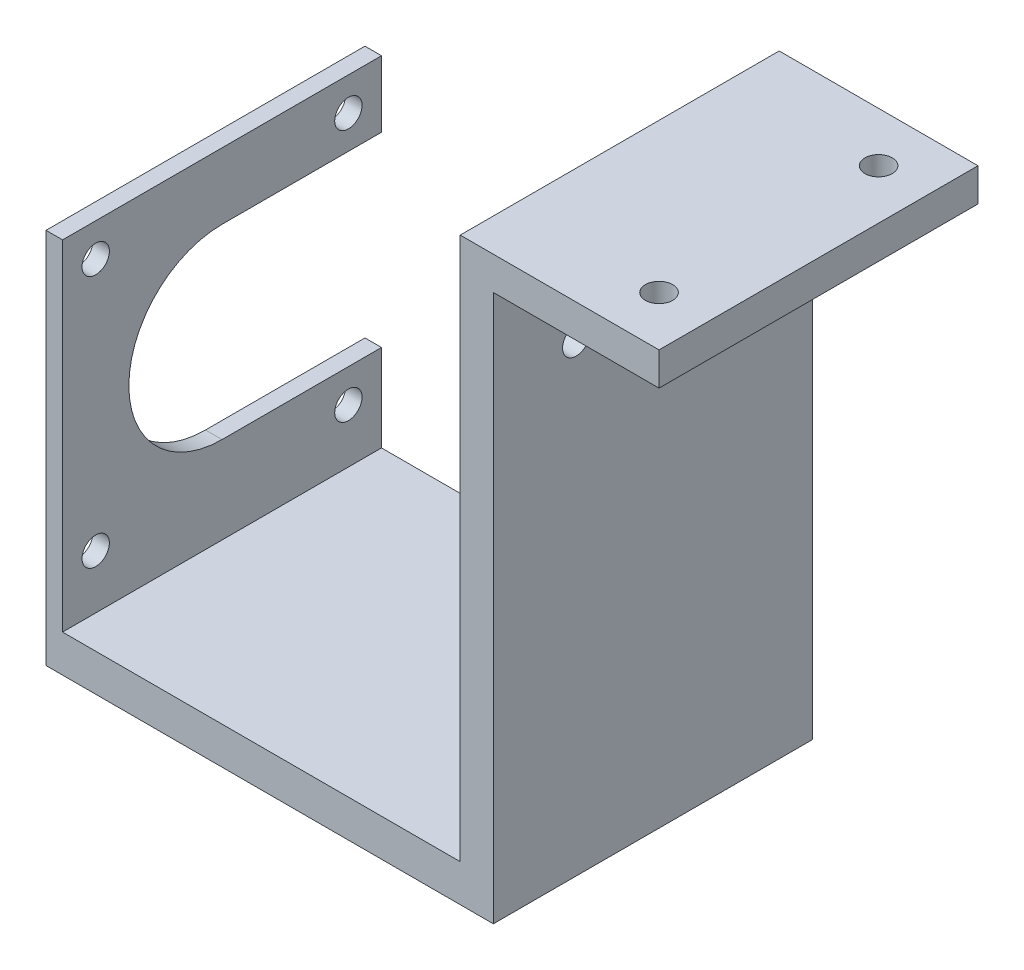
SolidWorks part; units mm, degrees
ref_plane "Front Plane" through (0, 0, 0) normal (0, 0, 1) x (1, 0, 0)
ref_plane "Top Plane" through (0, 0, 0) normal (0, 1, 0) x (1, 0, 0)
ref_plane "Right Plane" through (0, 0, 0) normal (1, 0, 0) x (0, 0, -1)
sketch "Sketch1" plane through (0, 0, 0) normal (1, 0, 0) x (0, 0, -1)
  line L1 (0, 0) -> (13, 0)
  line L2 (0, 0) -> (0, -16)
  line L3 (0, -16) -> (13, -16)
  line L4 (13, 0) -> (13, -16)
  dimension "D1" = 13
  dimension "D2" = 16
extrude "Boss-Extrude1" add sketch "Sketch1" along normal blind 4
sketch "Sketch2" plane through (4, 0, 0) normal (1, 0, 0) x (0, 0, -1)
  line L0 (13, 0) -> (0, 0) construction
  line L1 (0, -16) -> (13, -16) construction
  line L2 (13, -16) -> (13, 0) construction
  line L3 (0, 0) -> (0, -16) construction
  circle A0 centre (6.5, -4) radius 1.65
  circle A1 centre (6.5, -12) radius 1.65
  dimension "D1" = 3.3
  dimension "D2" = 3.3
  dimension "D3" = 4
  dimension "D4" = 4
  dimension "D5" = 6.5
  dimension "D6" = 6.5
extrude "Cut-Extrude1" cut sketch "Sketch2" against normal blind 10
sketch "Sketch3" plane through (0, -16, 0) normal (0, -1, 0) x (1, 0, 0)
  line L1 (4, 0) -> (0, 0)
  line L2 (4, 0) -> (4, -13)
  line L3 (4, -13) -> (0, -13)
  line L4 (0, 0) -> (0, -13)
extrude "Boss-Extrude2" add sketch "Sketch3" along normal blind 4
sketch "Sketch4" plane through (4, 0, 0) normal (1, 0, 0) x (0, 0, -1)
  line L0 (13, -20) -> (13, 0) construction
  line L1 (0, -20) -> (13, -20)
  line L2 (0, -20) -> (0, -16)
  line L3 (0, -16) -> (13, -16)
  line L4 (13, -20) -> (13, -16)
  dimension "D1" = 4
extrude "Boss-Extrude3" add sketch "Sketch4" along normal blind 60
sketch "Sketch6" plane through (0, -16, 0) normal (0, 1, 0) x (1, 0, 0)
  line L0 (64, 0) -> (4, 0) construction
  line L1 (64, 13) -> (60, 13)
  line L2 (64, 13) -> (64, -21)
  line L3 (64, -21) -> (60, -21)
  line L4 (60, 13) -> (60, -21)
  line L7 (64, 13) -> (60, 13)
  line L8 (64, 13) -> (64, 34)
  line L9 (64, 34) -> (60, 34)
  line L10 (60, 13) -> (60, 34)
  line M2 (4, 0) -> (64, 0)
  line M3 (64, 0) -> (64, 13)
  line M4 (64, 13) -> (4, 13)
  dimension "D1" = 4
  dimension "D2" = 21
  dimension "D3" = 21
extrude "Boss-Extrude4" add sketch "Sketch6" along normal blind 28 contours L4 L3 L2 M2 | L10 L8 L9 M4 | L4 M4 M2 M3
sketch "Sketch12" plane through (0, 0, -34) normal (0, 0, -1) x (-1, 0, 0)
  line L1 (-60, -16) -> (-64, -16)
  line L2 (-60, -16) -> (-60, 12)
  line L3 (-60, 12) -> (-64, 12)
  line L4 (-64, -16) -> (-64, 12)
extrude "Boss-Extrude8" add sketch "Sketch12" along normal blind 1.65
sketch "Sketch13" plane through (0, 0, 21) normal (0, 0, 1) x (1, 0, 0)
  line L1 (60, 12) -> (64, 12)
  line L2 (60, 12) -> (60, -16)
  line L3 (60, -16) -> (64, -16)
  line L4 (64, 12) -> (64, -16)
extrude "Boss-Extrude9" add sketch "Sketch13" along normal blind 1.65
sketch "Sketch14" plane through (0, 12, 0) normal (0, 1, 0) x (1, 0, 0)
  line L0 (64, 35.65) -> (64, -22.65) construction
  line L1 (64, 24.35) -> (60, 24.35)
  line L2 (64, 24.35) -> (64, -11.5284)
  line L3 (64, -11.5284) -> (60, -11.5284)
  line L4 (60, 24.35) -> (60, -11.5284)
  line L5 (60, 35.65) -> (60, -22.65) construction
  line L6 (64, -22.65) -> (60, -22.65) construction
  line L7 (60, 35.65) -> (64, 35.65) construction
  point P10 (62, -22.65)
  dimension "D1" = 11.3
  dimension "D2" = 11.3
extrude "Cut-Extrude5" cut sketch "Sketch14" against normal blind 24
sketch "Sketch15" plane through (64, 0, 0) normal (1, 0, 0) x (0, 0, -1)
  line L0 (-11.5284, 12) -> (-22.65, 12) construction
  line L1 (35.65, 12) -> (24.35, 12) construction
  line L2 (-22.65, -16) -> (-22.65, 12) construction
  line L3 (35.65, 12) -> (35.65, -16) construction
  circle A0 centre (-17, -11.5) radius 1.65
  circle A1 centre (30, -11.5) radius 1.65
  dimension "D1" = 3.3
  dimension "D2" = 3.3
  dimension "D3" = 23.5
  dimension "D4" = 23.5
  dimension "D5" = 5.65
  dimension "D6" = 5.65
extrude "Cut-Extrude6" cut sketch "Sketch15" against normal blind 24
sketch "Sketch16" plane through (0, 12, 0) normal (0, 1, 0) x (1, 0, 0)
  line L1 (60, -22.65) -> (64, -22.65)
  line L2 (60, -22.65) -> (60, -11.5284)
  line L3 (60, -11.5284) -> (64, -11.5284)
  line L4 (64, -22.65) -> (64, -11.5284)
  line L5 (60, 24.35) -> (64, 24.35)
  line L6 (60, 24.35) -> (60, 35.65)
  line L7 (60, 35.65) -> (64, 35.65)
  line L8 (64, 24.35) -> (64, 35.65)
extrude "Boss-Extrude10" add sketch "Sketch16" along normal blind 29.15
sketch "Sketch17" plane through (64, 0, 0) normal (1, 0, 0) x (0, 0, -1)
  line L0 (-22.65, -16) -> (-22.65, 41.15) construction
  line L1 (35.65, 41.15) -> (35.65, -16) construction
  line L2 (-22.65, 41.15) -> (-11.5284, 41.15) construction
  line L3 (24.35, 41.15) -> (35.65, 41.15) construction
  circle A0 centre (-17, 35.5) radius 1.65
  circle A1 centre (30, 35.5) radius 1.65
  dimension "D1" = 3.3
  dimension "D2" = 3.3
  dimension "D4" = 5.65
  dimension "D3" = 5.65
  dimension "D5" = 5.65
  dimension "D6" = 5.65
extrude "Cut-Extrude8" cut sketch "Sketch17" against normal blind 29.15
sketch "Sketch18" plane through (64, 0, 0) normal (1, 0, 0) x (0, 0, -1)
  line L1 (-22.65, -16) -> (13, -16)
  line L2 (-22.65, -16) -> (-22.65, -20)
  line L3 (-22.65, -20) -> (13, -20)
  line L4 (13, -16) -> (13, -20)
  line L5 (0, -20) -> (35.65, -20)
  line L6 (0, -20) -> (0, -16)
  line L7 (0, -16) -> (35.65, -16)
  line L8 (35.65, -20) -> (35.65, -16)
  line M9 (-22.65, -16) -> (0, -16)
  line M10 (0, -16) -> (0, -20)
  line M11 (0, -20) -> (13, -20)
  line M12 (13, -20) -> (13, -16)
  line M13 (13, -16) -> (35.65, -16)
extrude "Boss-Extrude11" add sketch "Sketch18" against normal blind 4 contours L2 L3 M10 M9 | L5 L8 M13 M12 | L1 M10 M11 M12
sketch "Sketch19" plane through (0, 0, -13) normal (0, 0, -1) x (-1, 0, 0)
  line L1 (0, -20) -> (-4, -20)
  line L2 (0, -20) -> (0, 0)
  line L3 (0, 0) -> (-4, 0)
  line L4 (-4, -20) -> (-4, 0)
extrude "Boss-Extrude12" add sketch "Sketch19" along normal blind 40
sketch "Sketch20" plane through (0, 0, 0) normal (-1, 0, 0) x (0, 0, 1)
  line L0 (-53, 0) -> (0, 0) construction
  line L1 (-53, -20) -> (-53, 0) construction
  circle A0 centre (-46.5, -4) radius 1.65
  circle A1 centre (-46.5, -12) radius 1.65
  dimension "D1" = 3.3
  dimension "D2" = 3.3
  dimension "D3" = 4
  dimension "D4" = 8
  dimension "D5" = 6.5
  dimension "D6" = 6.5
extrude "Cut-Extrude9" cut sketch "Sketch20" against normal blind 40
sketch "Sketch21" plane through (0, -16, 0) normal (0, 1, 0) x (1, 0, 0)
  line L0 (4, 53) -> (4, 13) construction
  line L1 (28, 21.75) -> (24, 21.75)
  line L2 (28, 21.75) -> (28, -8.75)
  line L3 (28, -8.75) -> (24, -8.75)
  line L4 (24, 21.75) -> (24, -8.75)
  line L5 (60, 13) -> (4, 13) construction
  line L6 (60, 0) -> (4, 0) construction
  dimension "D1" = 20
  dimension "D2" = 4
  dimension "D3" = 8.75
  dimension "D4" = 8.75
extrude "Boss-Extrude13" add sketch "Sketch21" along normal blind 38.5
sketch "Sketch23" plane through (0, 22.5, 0) normal (0, 1, 0) x (1, 0, 0)
  line L1 (24, 21.75) -> (28, 21.75)
  line L2 (24, 21.75) -> (24, 25.75)
  line L3 (24, 25.75) -> (28, 25.75)
  line L4 (28, 21.75) -> (28, 25.75)
  line L6 (24, 21.75) -> (24, -8.75) construction
  line L7 (28, -8.75) -> (28, 21.75) construction
  line L8 (24, -8.75) -> (28, -8.75)
  line L9 (24, -8.75) -> (24, -12.75)
  line L10 (24, -12.75) -> (28, -12.75)
  line L11 (28, -8.75) -> (28, -12.75)
  dimension "D1" = 4
  dimension "D2" = 4
  dimension "D3" = 4
  dimension "D4" = 0
extrude "Boss-Extrude14" add sketch "Sketch23" against normal blind 38.5
sketch "Sketch24" plane through (0, 22.5, 0) normal (0, 1, 0) x (1, 0, 0)
  line L1 (28, 25.75) -> (24, 25.75)
  line L2 (28, 25.75) -> (28, -12.75)
  line L3 (28, -12.75) -> (24, -12.75)
  line L4 (24, 25.75) -> (24, -12.75)
extrude "Boss-Extrude15" add sketch "Sketch24" along normal blind 3
sketch "Sketch25" plane through (28, 0, 0) normal (1, 0, 0) x (0, 0, -1)
  line L0 (25.75, -16) -> (25.75, 25.5) construction
  line L1 (25.75, -13) -> (-12.75, -13)
  line L2 (25.75, -13) -> (25.75, -20)
  line L3 (25.75, -20) -> (-12.75, -20)
  line L4 (-12.75, -13) -> (-12.75, -20)
  line L5 (13, -16) -> (25.75, -16) construction
  line L6 (-12.75, -16) -> (0, -16) construction
  line L7 (-12.75, -16) -> (-12.75, 25.5) construction
  dimension "D1" = 3
  dimension "D2" = 4
  dimension "D3" = 0
sketch "Sketch27" plane through (0, -20, 0) normal (0, -1, 0) x (1, 0, 0)
  line L1 (64, 22.65) -> (60, 22.65)
  line L2 (64, 22.65) -> (64, -35.65)
  line L3 (64, -35.65) -> (60, -35.65)
  line L4 (60, 22.65) -> (60, -35.65)
extrude "Cut-Extrude10" cut sketch "Sketch27" against normal blind 100
sketch "Sketch29" plane through (28, 0, 0) normal (1, 0, 0) x (0, 0, -1)
  line L2 (-12.75, -13) -> (25.75, -13)
  line L3 (-12.75, -13) -> (-12.75, -20)
  line L4 (-12.75, -20) -> (25.75, -20)
  line L5 (25.75, -13) -> (25.75, -20)
extrude "Boss-Extrude16" add sketch "Sketch29" along normal blind 40 and the other way blind 28
sketch "Sketch30" plane through (24, 0, 0) normal (-1, 0, 0) x (0, 0, 1)
  line L0 (12.75, -13) -> (12.75, 25.5) construction
  line L1 (-25.75, 25.5) -> (12.75, 25.5) construction
  line L2 (-25.75, -13) -> (12.75, -13) construction
  line L3 (-25.75, -13) -> (-25.75, 25.5) construction
  circle A0 centre (8.75, 21.5) radius 1.65
  circle A1 centre (8.75, -9) radius 1.65
  circle A2 centre (-21.75, 21.5) radius 1.65
  circle A3 centre (-21.75, -9) radius 1.65
  dimension "D1" = 3.3
  dimension "D4" = 3.3
  dimension "D7" = 3.3
  dimension "D12" = 3.3
  dimension "D2" = 4
  dimension "D3" = 4
  dimension "D5" = 4
  dimension "D6" = 4
  dimension "D8" = 4
  dimension "D9" = 4
  dimension "D10" = 4
  dimension "D11" = 4
extrude "Cut-Extrude11" cut sketch "Sketch30" against normal blind 40
sketch "Sketch31" plane through (0, 25.5, 0) normal (0, 1, 0) x (1, 0, 0)
  line L0 (28, -12.75) -> (28, 25.75) construction
  line L1 (28, 17.75) -> (24, 17.75)
  line L2 (28, 17.75) -> (28, -4.75)
  line L3 (28, -4.75) -> (24, -4.75)
  line L4 (24, 17.75) -> (24, -4.75)
  line L5 (24, 25.75) -> (24, -12.75) construction
  line L6 (24, -12.75) -> (28, -12.75) construction
  dimension "D1" = 8
  dimension "D2" = 8
extrude "Cut-Extrude12" cut sketch "Sketch31" against normal blind 38.5
sketch "Sketch32" plane through (68, 0, 0) normal (1, 0, 0) x (0, 0, -1)
  line L0 (25.75, -20) -> (25.75, -13) construction
  line L1 (-12.75, -13) -> (25.75, -13)
  line L2 (-12.75, -13) -> (-12.75, -15.5)
  line L3 (-12.75, -15.5) -> (25.75, -15.5)
  line L4 (25.75, -13) -> (25.75, -15.5)
  dimension "D1" = 2.5
extrude "Cut-Extrude13" cut sketch "Sketch32" against normal blind 40
sketch "Sketch33" plane through (0, 25.5, 0) normal (0, 1, 0) x (1, 0, 0)
  line L1 (24, -12.75) -> (28, -12.75)
  line L2 (24, -12.75) -> (24, -4.75)
  line L3 (24, -4.75) -> (28, -4.75)
  line L4 (28, -12.75) -> (28, -4.75)
  line L5 (24, 17.75) -> (28, 17.75)
  line L6 (24, 17.75) -> (24, 25.75)
  line L7 (24, 25.75) -> (28, 25.75)
  line L8 (28, 17.75) -> (28, 25.75)
extrude "Boss-Extrude17" add sketch "Sketch33" against normal blind 8
sketch "Sketch34" plane through (28, 0, 0) normal (1, 0, 0) x (0, 0, -1)
  line L0 (-12.75, 25.5) -> (-4.75, 25.5) construction
  line L1 (-12.75, -15.5) -> (-12.75, 25.5) construction
  line L2 (25.75, -15.5) -> (25.75, 25.5) construction
  line L3 (17.75, 25.5) -> (25.75, 25.5) construction
  circle A0 centre (-8.75, 21.5) radius 1.65
  circle A1 centre (21.75, 21.5) radius 1.65
  dimension "D1" = 3.3
  dimension "D2" = 3.3
  dimension "D3" = 4
  dimension "D4" = 4
  dimension "D5" = 4
  dimension "D6" = 4
extrude "Cut-Extrude14" cut sketch "Sketch34" against normal blind 8
sketch "Sketch35" plane through (0, -13, 0) normal (0, 1, 0) x (1, 0, 0)
  line L0 (0, -12.75) -> (24, -12.75) construction
  line L1 (10, -12.75) -> (14, -12.75)
  line L2 (10, -12.75) -> (10, 30.75)
  line L3 (10, 30.75) -> (14, 30.75)
  line L4 (14, -12.75) -> (14, 30.75)
  line L5 (24, 25.75) -> (24, 17.75) construction
  line L6 (4, 25.75) -> (24, 25.75) construction
  dimension "D1" = 10
  dimension "D2" = 4
  dimension "D3" = 5
extrude "Boss-Extrude18" add sketch "Sketch35" along normal blind 13
sketch "Sketch36" plane through (0, -20, 0) normal (0, -1, 0) x (1, 0, 0)
  line L1 (0, 12.75) -> (68, 12.75) construction
  line L2 (0, 12.75) -> (10, 12.75)
  line L3 (0, 12.75) -> (0, -67.25)
  line L4 (0, -67.25) -> (10, -67.25)
  line L5 (10, 12.75) -> (10, -67.25)
  line L6 (4, -53) -> (4, -25.75) construction
  dimension "D1" = 10
  dimension "D2" = 80
  dimension "D3" = 4
extrude "Cut-Extrude15" cut sketch "Sketch36" against normal up to vertex
sketch "Sketch37" plane through (10, 0, 0) normal (-1, 0, 0) x (0, 0, 1)
  line L1 (-30.75, -13) -> (-25.75, -13)
  line L2 (-30.75, -13) -> (-30.75, -20)
  line L3 (-30.75, -20) -> (-25.75, -20)
  line L4 (-25.75, -13) -> (-25.75, -20)
extrude "Boss-Extrude19" add sketch "Sketch37" against normal blind 4
sketch "Sketch41" plane through (14, 0, 0) normal (1, 0, 0) x (0, 0, -1)
  line L1 (25.75, -20) -> (38.75, -20)
  line L2 (25.75, -20) -> (25.75, 0)
  line L3 (25.75, 0) -> (38.75, 0)
  line L4 (38.75, -20) -> (38.75, 0)
  dimension "D1" = 13
  dimension "D2" = 20
extrude "Boss-Extrude20" add sketch "Sketch41" against normal blind 4
sketch "Sketch42" plane through (10, 0, 0) normal (-1, 0, 0) x (0, 0, 1)
  line L0 (-38.75, 0) -> (12.75, 0) construction
  line L1 (-38.75, -20) -> (-38.75, 0) construction
  circle A0 centre (-32.25, -4) radius 1.65
  circle A1 centre (-32.25, -12) radius 1.65
  dimension "D1" = 3.3
  dimension "D2" = 3.3
  dimension "D3" = 4
  dimension "D4" = 6.5
  dimension "D5" = 8
  dimension "D6" = 6.5
extrude "Cut-Extrude18" cut sketch "Sketch42" against normal blind 4
sketch "Sketch43" plane through (0, 0, 0) normal (0, 1, 0) x (1, 0, 0)
  line L0 (10, 38.75) -> (10, -12.75) construction
  line L1 (14, -12.75) -> (10, -12.75)
  line L2 (14, -12.75) -> (14, 25.75)
  line L3 (14, 25.75) -> (10, 25.75)
  line L4 (10, -12.75) -> (10, 25.75)
  line L5 (10, 38.75) -> (14, 38.75) construction
  dimension "D1" = 13
extrude "Cut-Extrude19" cut sketch "Sketch43" against normal blind 10
sketch "Sketch44" plane through (28, 0, 0) normal (1, 0, 0) x (0, 0, -1)
  line L0 (-4.75, -13) -> (-4.75, 25.5) construction
  line L1 (-12.75, -15.5) -> (-4.75, -15.5)
  line L2 (-12.75, -15.5) -> (-12.75, -6.5)
  line L3 (-12.75, -6.5) -> (-4.75, -6.5)
  line L4 (-4.75, -15.5) -> (-4.75, -6.5)
  line L5 (17.75, -13) -> (17.75, 25.5) construction
  line L6 (25.75, -15.5) -> (17.75, -15.5)
  line L7 (25.75, -15.5) -> (25.75, -6.5)
  line L8 (25.75, -6.5) -> (17.75, -6.5)
  line L9 (17.75, -15.5) -> (17.75, -6.5)
  dimension "D1" = 9
  dimension "D2" = 9
extrude "Boss-Extrude21" add sketch "Sketch44" against normal blind 4
sketch "Sketch45" plane through (24, 0, 0) normal (-1, 0, 0) x (0, 0, 1)
  line L0 (4.75, -13) -> (12.75, -13) construction
  line L1 (-25.75, -13) -> (-17.75, -13) construction
  line L2 (-25.75, -13) -> (-25.75, 25.5) construction
  line L3 (12.75, -13) -> (12.75, 25.5) construction
  circle A0 centre (-21.75, -7) radius 1.65
  circle A1 centre (8.75, -7) radius 1.65
  dimension "D1" = 3.3
  dimension "D2" = 3.3
  dimension "D3" = 6
  dimension "D4" = 6
  dimension "D5" = 4
  dimension "D6" = 4
extrude "Cut-Extrude20" cut sketch "Sketch45" against normal blind 4
sketch "Sketch46" plane through (0, -15.5, 0) normal (0, 1, 0) x (1, 0, 0)
  line L0 (68, -12.75) -> (68, 25.75) construction
  line L1 (64, 18.2859) -> (67, 20.0179)
  line L2 (67, 20.0179) -> (67, 23.4821)
  line L3 (67, 23.4821) -> (64, 25.2141)
  line L4 (64, 25.2141) -> (61, 23.4821)
  line L5 (61, 23.4821) -> (61, 20.0179)
  line L6 (61, 20.0179) -> (64, 18.2859)
  line L7 (64, -12.2141) -> (67, -10.4821)
  line L8 (67, -10.4821) -> (67, -7.0179)
  line L9 (67, -7.0179) -> (64, -5.2859)
  line L10 (64, -5.2859) -> (61, -7.0179)
  line L11 (61, -7.0179) -> (61, -10.4821)
  line L12 (61, -10.4821) -> (64, -12.2141)
  line L13 (28, 25.75) -> (68, 25.75) construction
  line L14 (28, -12.75) -> (68, -12.75) construction
  circle A0 centre (64, 21.75) radius 3 construction
  circle A1 centre (64, -8.75) radius 3 construction
  dimension "D3" = 6
  dimension "D7" = 6
  dimension "D1" = 4
  dimension "D2" = 4
  dimension "D4" = 1
  dimension "D5" = 4
  dimension "D6" = 4
  dimension "D8" = 1
extrude "Cut-Extrude21" cut sketch "Sketch46" against normal blind 3
sketch "Sketch49" plane through (0, -15.5, 0) normal (0, 1, 0) x (1, 0, 0)
  line L0 (68, -12.75) -> (68, 25.75) construction
  line L1 (28, 25.75) -> (68, 25.75) construction
  line L2 (28, -12.75) -> (68, -12.75) construction
  circle A0 centre (64, 21.75) radius 1.65
  circle A1 centre (64, -8.75) radius 1.65
  dimension "D1" = 3.3
  dimension "D2" = 3.3
  dimension "D3" = 4
  dimension "D4" = 4
  dimension "D5" = 4
  dimension "D6" = 4
extrude "Cut-Extrude22" cut sketch "Sketch49" against normal blind 5
ref_plane "Plane1" through (10, -10, -25.75) normal (0, 0, 1) x (1, 0, 0)
sketch "Sketch54" plane through (0, -10, 0) normal (0, 1, 0) x (1, 0, 0)
  line L0 (10, -12.75) -> (14, -12.75) construction
  line L1 (10, 25.75) -> (11, 25.75)
  line L2 (10, 25.75) -> (10, -12.75)
  line L3 (10, -12.75) -> (11, -12.75)
  line L4 (11, 25.75) -> (11, -12.75)
  dimension "D1" = 1
  dimension "D2" = 0
extrude "Cut-Extrude24" cut sketch "Sketch54" against normal blind 50
sketch "Sketch55" plane through (24, 0, 0) normal (-1, 0, 0) x (0, 0, 1)
  line L0 (4.75, -13) -> (4.75, 25.5) construction
  line L1 (12.75, -13) -> (4.75, -13)
  line L2 (12.75, -13) -> (12.75, -3)
  line L3 (12.75, -3) -> (4.75, -3)
  line L4 (4.75, -13) -> (4.75, -3)
  line L5 (-25.75, -13) -> (-25.75, 25.5) construction
  line L6 (-17.75, -13) -> (-25.75, -13)
  line L7 (-17.75, -13) -> (-17.75, -3)
  line L8 (-17.75, -3) -> (-25.75, -3)
  line L9 (-25.75, -13) -> (-25.75, -3)
  dimension "D1" = 10
  dimension "D2" = 10
extrude "Boss-Extrude22" add sketch "Sketch55" against normal blind 4
sketch "Sketch56" plane through (24, 0, 0) normal (-1, 0, 0) x (0, 0, 1)
  line L0 (-17.75, -13) -> (-17.75, 25.5) construction
  line L1 (4.75, -13) -> (4.75, 25.5) construction
  circle A0 centre (-21.75, -9) radius 1.65
  circle A1 centre (8.75, -9) radius 1.65
  circle A2 centre (-21.75, 21.5) radius 1.65 construction
  circle A3 centre (8.75, 21.5) radius 1.65 construction
  dimension "D3" = 3.3
  dimension "D4" = 3.3
  dimension "D1" = 30.5
  dimension "D2" = 30.5
  dimension "D5" = 4
  dimension "D6" = 4
extrude "Cut-Extrude25" cut sketch "Sketch56" against normal blind 4
sketch "Sketch57" plane through (0, -13, 0) normal (0, 1, 0) x (1, 0, 0)
  line L1 (24, -12.75) -> (-1, -12.75)
  line L2 (24, -12.75) -> (24, 57.25)
  line L3 (24, 57.25) -> (-1, 57.25)
  line L4 (-1, -12.75) -> (-1, 57.25)
  dimension "D1" = 70
  dimension "D2" = 25
extrude "Cut-Extrude26" cut sketch "Sketch57" against normal blind 10 and the other way blind 15
sketch "Sketch58" plane through (0, -20, 0) normal (0, -1, 0) x (1, 0, 0)
  line L0 (28, -25.75) -> (28, 12.75) construction
  line L1 (28, -25.75) -> (75.5, -25.75)
  line L2 (28, -25.75) -> (28, 12.75)
  line L3 (28, 12.75) -> (75.5, 12.75)
  line L4 (75.5, -25.75) -> (75.5, 12.75)
  line L5 (24, -25.75) -> (68, -25.75) construction
  dimension "D1" = 38.5
  dimension "D2" = 47.5
extrude "Boss-Extrude24" add sketch "Sketch58" against normal blind 4.5
sketch "Sketch59" plane through (0, -20, 0) normal (0, -1, 0) x (1, 0, 0)
  line L0 (24, -25.75) -> (75.5, -25.75) construction
  line L1 (75.5, 12.75) -> (76, 12.75)
  line L2 (75.5, 12.75) -> (75.5, -25.75)
  line L3 (75.5, -25.75) -> (76, -25.75)
  line L4 (76, 12.75) -> (76, -25.75)
  dimension "D1" = 0
  dimension "D2" = 0.5
extrude "Boss-Extrude25" add sketch "Sketch59" against normal blind 4.5
sketch "Sketch60" plane through (0, -20, 0) normal (0, -1, 0) x (1, 0, 0)
  line L0 (24, -25.75) -> (76, -25.75) construction
  line L1 (76, 12.75) -> (80, 12.75)
  line L2 (76, 12.75) -> (76, -25.75)
  line L3 (76, -25.75) -> (80, -25.75)
  line L4 (80, 12.75) -> (80, -25.75)
  dimension "D1" = 0
  dimension "D2" = 4
extrude "Boss-Extrude26" add sketch "Sketch60" against normal blind 69.5
sketch "Sketch61" plane through (80, 0, 0) normal (1, 0, 0) x (0, 0, -1)
  line L0 (-12.75, 49.5) -> (-12.75, -20) construction
  line L1 (25.75, 49.5) -> (-12.75, 49.5)
  line L2 (25.75, 49.5) -> (25.75, 47.0423)
  line L3 (25.75, 47.0423) -> (-12.75, 47.0423)
  line L4 (-12.75, 49.5) -> (-12.75, 47.0423)
extrude "Boss-Extrude27" add sketch "Sketch61" along normal blind 20
sketch "Sketch62" plane through (76, 0, 0) normal (-1, 0, 0) x (0, 0, 1)
  line L0 (12.75, 49.5) -> (12.75, -15.5) construction
  line L1 (12.75, 28) -> (-25.75, 28)
  line L2 (12.75, 28) -> (12.75, 30)
  line L3 (12.75, 30) -> (-25.75, 30)
  line L4 (-25.75, 28) -> (-25.75, 30)
  line L5 (-25.75, 49.5) -> (-25.75, -15.5) construction
  line L6 (-25.75, -15.5) -> (12.75, -15.5) construction
  dimension "D1" = 43.5
  dimension "D2" = 2
extrude "Boss-Extrude31" add sketch "Sketch62" along normal blind 29.5
sketch "Sketch64" plane through (0, 30, 0) normal (0, 1, 0) x (1, 0, 0)
  line L0 (46.5, -12.75) -> (46.5, 25.75) construction
  line L1 (46.5, 0) -> (50.5, 0)
  line L2 (46.5, 0) -> (46.5, 13)
  line L3 (46.5, 13) -> (50.5, 13)
  line L4 (50.5, 0) -> (50.5, 13)
  line L5 (46.5, -12.75) -> (76, -12.75) construction
  dimension "D1" = 12.75
  dimension "D2" = 13
  dimension "D3" = 4
extrude "Boss-Extrude32" add sketch "Sketch64" along normal blind 16
sketch "Sketch65" plane through (46.5, 0, 0) normal (-1, 0, 0) x (0, 0, 1)
  line L0 (-13, 46) -> (0, 46) construction
  line L1 (-13, 46) -> (-13, 30) construction
  line L2 (0, 46) -> (0, 30) construction
  circle A0 centre (-6.5, 34) radius 1.65
  circle A1 centre (-6.5, 42) radius 1.65
  dimension "D3" = 3.3
  dimension "D6" = 3.3
  dimension "D1" = 4
  dimension "D2" = 6.5
  dimension "D4" = 6.5
  dimension "D5" = 8
extrude "Cut-Extrude27" cut sketch "Sketch65" against normal blind 16
sketch "Sketch66" plane through (0, 0, -25.75) normal (0, 0, -1) x (-1, 0, 0)
  line L1 (-76, 49.5) -> (-100, 49.5)
  line L2 (-76, 49.5) -> (-76, 50)
  line L3 (-76, 50) -> (-100, 50)
  line L4 (-100, 49.5) -> (-100, 50)
  dimension "D1" = 0.5
extrude "Boss-Extrude33" add sketch "Sketch66" against normal blind 38.5
sketch "Sketch67" plane through (0, 47.0423, 0) normal (0, -1, 0) x (1, 0, 0)
  line L1 (80, -25.75) -> (100, -25.75)
  line L2 (80, -25.75) -> (80, 12.75)
  line L3 (80, 12.75) -> (100, 12.75)
  line L4 (100, -25.75) -> (100, 12.75)
sketch "Sketch69" plane through (0, 47.0423, 0) normal (0, -1, 0) x (1, 0, 0)
  line L1 (80, -25.75) -> (100, -25.75)
  line L2 (80, -25.75) -> (80, 12.75)
  line L3 (80, 12.75) -> (100, 12.75)
  line L4 (100, -25.75) -> (100, 12.75)
extrude "Boss-Extrude34" add sketch "Sketch69" along normal blind 1.04
sketch "Sketch70" plane through (0, 46.0023, 0) normal (0, -1, 0) x (1, 0, 0)
  line L0 (100, -25.75) -> (100, 12.75) construction
  line L1 (80, 12.75) -> (100, 12.75) construction
  line L2 (80, -25.75) -> (100, -25.75) construction
  circle A0 centre (94, 6.75) radius 1.65
  circle A1 centre (94, -19.75) radius 1.65
  dimension "D5" = 3.3
  dimension "D6" = 3.3
  dimension "D1" = 6
  dimension "D2" = 6
  dimension "D3" = 6
  dimension "D4" = 6
extrude "Cut-Extrude29" cut sketch "Sketch70" against normal blind 10
sketch "Sketch72" plane through (0, -20, 0) normal (0, -1, 0) x (1, 0, 0)
  line L0 (24, -25.75) -> (80, -25.75) construction
  line L1 (24, 12.75) -> (26, 12.75)
  line L2 (24, 12.75) -> (24, -25.75)
  line L3 (24, -25.75) -> (26, -25.75)
  line L4 (26, 12.75) -> (26, -25.75)
  dimension "D1" = 2
extrude "Cut-Extrude31" cut sketch "Sketch72" against normal blind 60
sketch "Sketch73" plane through (26, 0, 0) normal (-1, 0, 0) x (0, 0, 1)
  line L0 (-25.75, 25.5) -> (-17.75, 25.5) construction
  line L1 (4.75, -13) -> (-17.75, -13)
  line L2 (4.75, -13) -> (4.75, 25.5)
  line L3 (4.75, 25.5) -> (-17.75, 25.5)
  line L4 (-17.75, -13) -> (-17.75, 25.5)
  line L5 (-17.75, 25.5) -> (-17.75, -13) construction
extrude "Boss-Extrude35" add sketch "Sketch73" against normal blind 2
sketch "Sketch74" plane through (26, 0, 0) normal (-1, 0, 0) x (0, 0, 1)
  line L0 (-25.75, 25.5) -> (12.75, 25.5) construction
  line L1 (12.75, 25.5) -> (12.75, -20) construction
  circle A0 centre (-6.5, 6.25) radius 11.25
  dimension "D3" = 22.5
  dimension "D1" = 19.25
  dimension "D2" = 19.25
extrude "Cut-Extrude32" cut sketch "Sketch74" against normal blind 2
sketch "Sketch75" plane through (26, 0, 0) normal (-1, 0, 0) x (0, 0, 1)
  line L0 (-25.75, 25.5) -> (-25.75, -20) construction
  line L1 (-6.5, 6.25) -> (-25.75, 6.25)
  line L2 (-6.5, 6.25) -> (-6.5, 17.5)
  line L3 (-6.5, 17.5) -> (-25.75, 17.5)
  line L4 (-25.75, 6.25) -> (-25.75, 17.5)
  line L6 (-6.5, 6.25) -> (-25.75, 6.25)
  line L7 (-6.5, 6.25) -> (-6.5, -5)
  line L8 (-6.5, -5) -> (-25.75, -5)
  line L9 (-25.75, 6.25) -> (-25.75, -5)
  circle M3 centre (-6.5, 6.25) radius 11.25
  line M5 (-25.75, 25.5) -> (-25.75, -20)
  dimension "D1" = 11.25
  dimension "D2" = 11.25
extrude "Cut-Extrude33" cut sketch "Sketch75" against normal blind 2 contours L3 L1 M3 M5 | L8 L1 M3 M5
sketch "Sketch76" plane through (76, 0, 0) normal (-1, 0, 0) x (0, 0, 1)
  line L0 (12.75, 30) -> (-25.75, 30) construction
  line L1 (12.75, 50) -> (12.75, 30) construction
  line L2 (-25.75, 50) -> (-25.75, 30) construction
  circle A0 centre (2.75, 36) radius 1.65
  circle A1 centre (-15.75, 36) radius 1.65
  dimension "D3" = 3.3
  dimension "D6" = 3.3
  dimension "D1" = 6
  dimension "D2" = 10
  dimension "D4" = 6
  dimension "D5" = 10
extrude "Cut-Extrude34" cut sketch "Sketch76" against normal blind 5
sketch "Sketch77" plane through (0, 0, 12.75) normal (0, 0, 1) x (1, 0, 0)
  line L1 (76, 28) -> (41, 28)
  line L2 (76, 28) -> (76, 58)
  line L3 (76, 58) -> (41, 58)
  line L4 (41, 28) -> (41, 58)
  dimension "D1" = 35
  dimension "D2" = 30
extrude "Cut-Extrude35" cut sketch "Sketch77" against normal blind 1000
